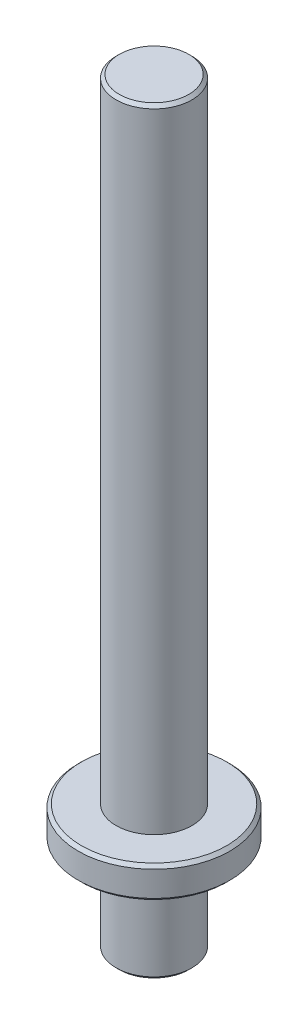
SolidWorks part; units mm, degrees
ref_plane "前视基准面" through (0, 0, 0) normal (0, 0, 1) x (1, 0, 0)
ref_plane "上视基准面" through (0, 0, 0) normal (0, 1, 0) x (1, 0, 0)
ref_plane "右视基准面" through (0, 0, 0) normal (1, 0, 0) x (0, 0, -1)
other "Configuration Table"
sketch "草图1" plane through (0, 0, 0) normal (0, 1, 0) x (1, 0, 0)
  circle A0 centre (0, 0) radius 6
  dimension "D1" = 12
extrude "凸台-拉伸1" add sketch "草图1" along normal blind 120
cosmetic thread "装饰螺纹线1" parameters "D1"=59.59, "D2"=10.072
sketch "草图2" plane through (0, 0, 0) normal (1, 0, 0) x (0, 0, -1)
  line L0 (0, 0) -> (0, 20) construction
  line L1 (0, 20) -> (12, 20)
  line L2 (12, 20) -> (12, 15)
  line L3 (12, 15) -> (0, 15)
  line L4 (-6, 0) -> (6, 0) construction
  line L5 (0, 20) -> (0, 15)
  dimension "D1" = 15
  dimension "D2" = 5
  dimension "D3" = 12
revolve "旋转1" add sketch "草图2" angle 360 about L0
chamfer "倒角1" distance 0.5 angle 45 4 edges at (0, 0, 6) (0, 15, -12) (0, 20, -12) (0, 120, 6)
